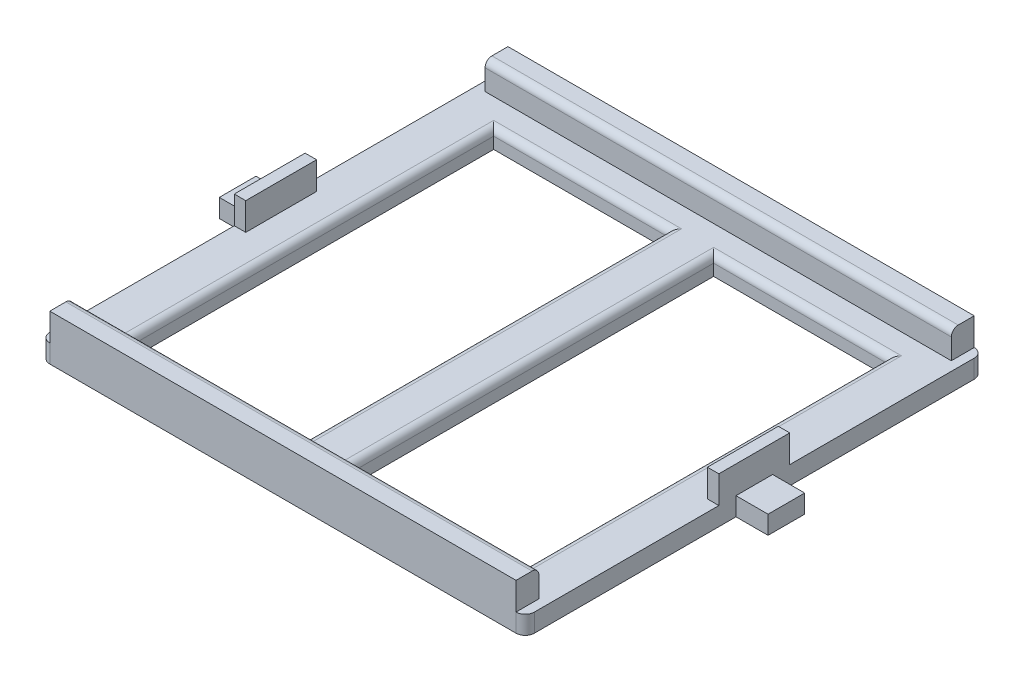
SolidWorks part; units mm, degrees
ref_plane "Front" through (0, 0, 0) normal (0, 0, 1) x (1, 0, 0)
ref_plane "Top" through (0, 0, 0) normal (0, 1, 0) x (1, 0, 0)
ref_plane "Right" through (0, 0, 0) normal (1, 0, 0) x (0, 0, -1)
sketch "Croquis1" plane through (0, 0, 0) normal (0, 1, 0) x (1, 0, 0)
  line L0 (-552.4462, 0) -> (27069.8637, 0) construction
  line L1 (0, -552.4462) -> (0, 27069.8637) construction
  line L2 (26.44, -25) -> (-26.44, -25)
  line L3 (-26.44, -25) -> (-26.44, -2)
  line L4 (-26.44, -2) -> (-29.94, -2)
  line L5 (-29.94, -2) -> (-29.94, 2)
  line L6 (-29.94, 2) -> (-26.44, 2)
  line L7 (-26.44, 2) -> (-26.44, 25)
  line L8 (-26.44, 25) -> (26.44, 25)
  line L9 (29.94, -2) -> (29.94, 2)
  line L10 (26.44, -2) -> (29.94, -2)
  line L11 (29.94, 2) -> (26.44, 2)
  line L12 (26.44, 2) -> (26.44, 25)
  line L13 (26.44, -25) -> (26.44, -2)
  line L14 (12, -552.4462) -> (12, 27069.8637) construction
  line L15 (-12, -552.4462) -> (-12, 27069.8637) construction
  line L16 (21.5, -20.5) -> (21.5, 19.5)
  line L17 (-21.5, -20.5) -> (-2.5, -20.5)
  line L18 (-21.5, -20.5) -> (-21.5, 19.5)
  line L19 (-21.5, 19.5) -> (-2.5, 19.5)
  line L20 (-2.5, -20.5) -> (-2.5, 19.5)
  line L21 (-21.5, -20.5) -> (-2.5, 19.5) construction
  line L22 (-21.5, 19.5) -> (-2.5, -20.5) construction
  line L23 (21.5, -20.5) -> (2.5, -20.5)
  line L24 (2.5, -20.5) -> (2.5, 19.5)
  line L25 (21.5, 19.5) -> (2.5, 19.5)
  point P4 (0, 25)
  point P19 (0, -25)
  point P23 (-12.9818, 0)
  dimension "D1" = 26.44
  dimension "D2" = 26.44
  dimension "D3" = 4
  dimension "D4" = 2
  dimension "D5" = 25
  dimension "D6" = 25
  dimension "D7" = 3.5
  dimension "D8" = 12
  dimension "D10" = 40
  dimension "D11" = 19
  dimension "D9" = 12
extrude "Saliente-Extruir1" add sketch "Croquis1" along normal blind 2
fillet "Redondeo1" radius 1 4 edges at (-26.44, 1, -25) (26.44, 1, -25) (26.44, 1, 25) (-26.44, 1, 25)
sketch "Croquis2" plane through (0, 2, 0) normal (0, 1, 0) x (1, 0, 0)
  line L0 (-1000, 0) -> (49000, 0) construction
  line L1 (-25.44, 25) -> (25.44, 25)
  line L2 (-25.44, 25) -> (-25.44, 22.5)
  line L3 (-25.44, 22.5) -> (25.44, 22.5)
  line L4 (25.44, 25) -> (25.44, 22.5)
  line L5 (-25.44, -25) -> (-25.44, -22.5)
  line L6 (-25.44, -22.5) -> (25.44, -22.5)
  line L7 (25.44, -25) -> (25.44, -22.5)
  line L8 (-25.44, -25) -> (25.44, -25)
  line L9 (-26.44, 24) -> (-26.44, 2) construction
  line L10 (-26.44, -3.8667) -> (-25.19, -3.8667)
  line L11 (-26.44, -3.8667) -> (-26.44, 3.8667)
  line L12 (-26.44, 3.8667) -> (-25.19, 3.8667)
  line L13 (-25.19, -3.8667) -> (-25.19, 3.8667)
  line L14 (-26.44, -3.8667) -> (-25.19, 3.8667) construction
  line L15 (-26.44, 3.8667) -> (-25.19, -3.8667) construction
  line L16 (0, -1000) -> (0, 49000) construction
  line L17 (26.44, -3.8667) -> (26.44, 3.8667)
  line L18 (26.44, -3.8667) -> (25.19, -3.8667)
  line L19 (25.19, -3.8667) -> (25.19, 3.8667)
  line L20 (26.44, 3.8667) -> (25.19, 3.8667)
  point P12 (-25.815, 0)
  dimension "D1" = 2.5
  dimension "D2" = 1.25
  dimension "D3" = 0
extrude "Saliente-Extruir2" add sketch "Croquis2" along normal blind 3
fillet "Redondeo2" radius 0.75 10 edges at (0, 5, -22.5) (0, 5, 22.5) (12, 2, 20.5) (21.5, 2, 0.5) (12, 2, -19.5) (2.5, 2, 0.5) (-12, 2, 20.5) (-2.5, 2, 0.5) (-12, 2, -19.5) (-21.5, 2, 0.5)
